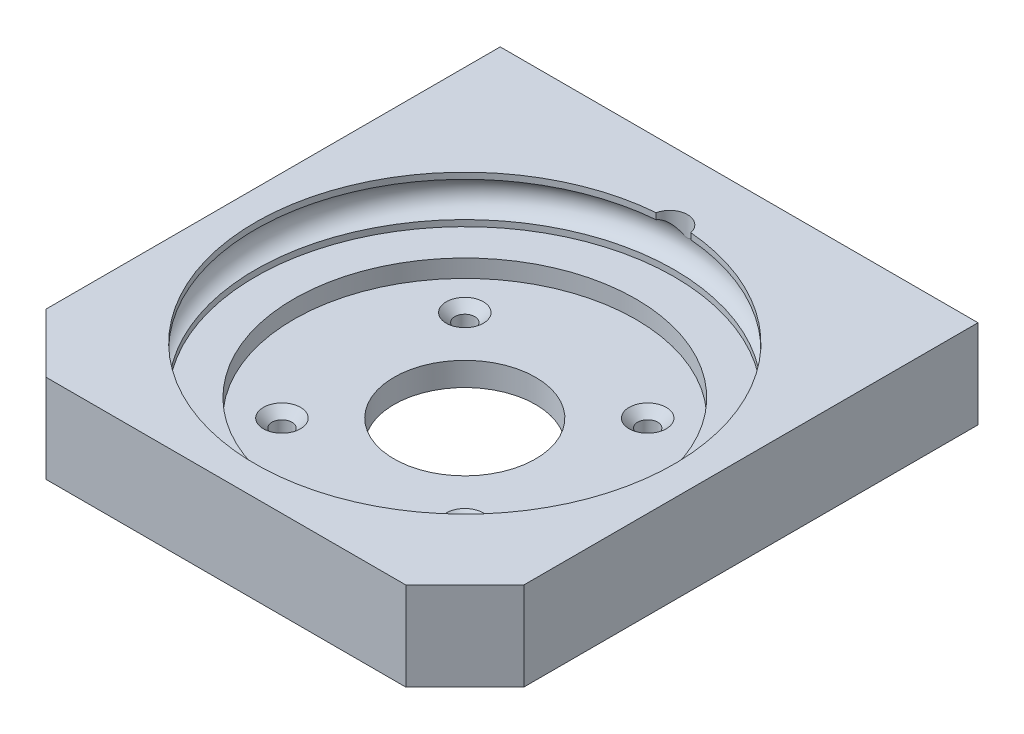
SolidWorks part; units mm, degrees
ref_plane "Front Plane" through (0, 0, 0) normal (0, 0, 1) x (1, 0, 0)
ref_plane "Top Plane" through (0, 0, 0) normal (0, 1, 0) x (1, 0, 0)
ref_plane "Right Plane" through (0, 0, 0) normal (1, 0, 0) x (0, 0, -1)
sketch "Sketch2" plane through (0, 0, 0) normal (0, 0, 1) x (1, 0, 0)
  line L0 (-29, 3) -> (-29, 0)
  line L1 (-29, 0) -> (-12, 0)
  line L2 (-12, 0) -> (-12, -4)
  line L3 (-12, -4) -> (-40.5, -4)
  line L4 (0, 0) -> (0, 12.8376) construction
  line L6 (-29, 3) -> (-35.5, 3)
  line L7 (-35.5, 3) -> (-35.5, 11)
  line L8 (-35.5, 11) -> (-40.5, 11)
  line L9 (-40.5, 11) -> (-40.5, -4)
  dimension "D1" = 24
  dimension "D2" = 58
  dimension "D3" = 71
  dimension "D4" = 5
  dimension "D5" = 4
  dimension "D6" = 3
  dimension "D7" = 8
revolve "Revolve1" add sketch "Sketch2" angle 360 about L4
sketch "Sketch3" plane through (0, 0, 0) normal (0, 1, 0) x (1, 0, 0)
  line L1 (-13, -13) -> (13, -13) construction
  line L2 (-13, -13) -> (-13, 13) construction
  line L3 (-13, 13) -> (13, 13) construction
  line L4 (13, -13) -> (13, 13) construction
  line L5 (-13, -13) -> (13, 13) construction
  line L6 (-13, 13) -> (13, -13) construction
  line L7 (-15.5, -15.5) -> (15.5, -15.5) construction
  line L8 (-15.5, -15.5) -> (-15.5, 15.5) construction
  line L9 (-15.5, 15.5) -> (15.5, 15.5) construction
  line L10 (15.5, -15.5) -> (15.5, 15.5) construction
  line L11 (-15.5, -15.5) -> (15.5, 15.5) construction
  line L12 (-15.5, 15.5) -> (15.5, -15.5) construction
  circle A0 centre (-13, 13) radius 1.25 construction
  circle A1 centre (13, 13) radius 1.25 construction
  circle A2 centre (13, -13) radius 1.25 construction
  circle A3 centre (-13, -13) radius 1.25 construction
  circle A4 centre (-15.5, 15.5) radius 1.25
  circle A5 centre (15.5, 15.5) radius 1.25
  circle A6 centre (15.5, -15.5) radius 1.25
  circle A7 centre (-15.5, -15.5) radius 1.25
  point P0 (0, 0)
  point P10 (0, 0)
  dimension "D2" = 2.5
  dimension "D1" = 26
  dimension "D3" = 31
extrude "Cut-Extrude1" cut sketch "Sketch3" against normal through all
sketch "Sketch4" plane through (0, 11, 0) normal (0, 1, 0) x (1, 0, 0)
  circle A0 centre (0, 0) radius 35.5
  circle A1 centre (0, 35.5) radius 1
  circle A2 centre (2.0823, 35.7208) radius 1
  circle A3 centre (4.1749, 35.7958) radius 1
  circle A4 centre (6.2677, 35.7247) radius 1
  circle A5 centre (8.3504, 35.5077) radius 1
  circle A6 centre (10.4129, 35.146) radius 1
  circle A7 centre (12.4451, 34.6413) radius 1
  circle A8 centre (14.4372, 33.9961) radius 1
  circle A9 centre (16.3794, 33.2135) radius 1
  circle A10 centre (18.2623, 32.2973) radius 1
  circle A11 centre (20.0767, 31.252) radius 1
  circle A12 centre (21.8138, 30.0827) radius 1
  circle A13 centre (23.465, 28.795) radius 1
  circle A14 centre (25.0225, 27.3953) radius 1
  circle A15 centre (26.4785, 25.8904) radius 1
  circle A16 centre (27.8259, 24.2876) radius 1
  circle A17 centre (29.0583, 22.5947) radius 1
  circle A18 centre (30.1696, 20.8199) radius 1
  circle A19 centre (31.1543, 18.972) radius 1
  circle A20 centre (32.0078, 17.0598) radius 1
  circle A21 centre (32.7258, 15.0928) radius 1
  circle A22 centre (33.3049, 13.0805) radius 1
  circle A23 centre (33.7421, 11.0327) radius 1
  circle A24 centre (34.0355, 8.9593) radius 1
  circle A25 centre (34.1835, 6.8706) radius 1
  circle A26 centre (34.1854, 4.7766) radius 1
  circle A27 centre (34.0413, 2.6876) radius 1
  circle A28 centre (33.7518, 0.6138) radius 1
  circle A29 centre (33.3183, -1.4348) radius 1
  circle A30 centre (32.743, -3.4482) radius 1
  circle A31 centre (32.0286, -5.4166) radius 1
  circle A32 centre (31.1787, -7.3303) radius 1
  circle A33 centre (30.1974, -9.1801) radius 1
  circle A34 centre (29.0894, -10.9569) radius 1
  circle A35 centre (27.8602, -12.6521) radius 1
  circle A36 centre (26.5157, -14.2574) radius 1
  circle A37 centre (25.0625, -15.765) radius 1
  circle A38 centre (23.5076, -17.1676) radius 1
  circle A39 centre (21.8588, -18.4583) radius 1
  circle A40 centre (20.1239, -19.6309) radius 1
  circle A41 centre (18.3114, -20.6795) radius 1
  circle A42 centre (16.4302, -21.5992) radius 1
  circle A43 centre (14.4894, -22.3854) radius 1
  circle A44 centre (12.4986, -23.0343) radius 1
  circle A45 centre (10.4673, -23.5428) radius 1
  circle A46 centre (8.4054, -23.9083) radius 1
  circle A47 centre (6.3232, -24.1291) radius 1
  circle A48 centre (4.2305, -24.2041) radius 1
  circle A49 centre (2.1378, -24.133) radius 1
  circle A50 centre (0.0551, -23.9161) radius 1
  circle A51 centre (-2.0074, -23.5544) radius 1
  circle A52 centre (-4.0397, -23.0497) radius 1
  circle A53 centre (-6.0318, -22.4044) radius 1
  circle A54 centre (-7.974, -21.6218) radius 1
  circle A55 centre (-9.8569, -20.7056) radius 1
  circle A56 centre (-11.6713, -19.6603) radius 1
  circle A57 centre (-13.4083, -18.491) radius 1
  circle A58 centre (-15.0596, -17.2034) radius 1
  circle A59 centre (-16.617, -15.8037) radius 1
  circle A60 centre (-18.073, -14.2987) radius 1
  circle A61 centre (-19.4205, -12.6959) radius 1
  circle A62 centre (-20.6528, -11.003) radius 1
  circle A63 centre (-21.7641, -9.2282) radius 1
  circle A64 centre (-22.7489, -7.3803) radius 1
  circle A65 centre (-23.6024, -5.4681) radius 1
  circle A66 centre (-24.3204, -3.5011) radius 1
  circle A67 centre (-24.8994, -1.4888) radius 1
  circle A68 centre (-25.3367, 0.559) radius 1
  circle A69 centre (-25.63, 2.6323) radius 1
  circle A70 centre (-25.778, 4.7211) radius 1
  circle A71 centre (-25.78, 6.815) radius 1
  circle A72 centre (-25.6358, 8.904) radius 1
  circle A73 centre (-25.3463, 10.9779) radius 1
  circle A74 centre (-24.9129, 13.0265) radius 1
  circle A75 centre (-24.3376, 15.0399) radius 1
  circle A76 centre (-23.6232, 17.0083) radius 1
  circle A77 centre (-22.7733, 18.922) radius 1
  circle A78 centre (-21.7919, 20.7718) radius 1
  circle A79 centre (-20.6839, 22.5486) radius 1
  circle A80 centre (-19.4547, 24.2438) radius 1
  circle A81 centre (-18.1102, 25.8491) radius 1
  circle A82 centre (-16.657, 27.3567) radius 1
  circle A83 centre (-15.1022, 28.7593) radius 1
  circle A84 centre (-13.4533, 30.05) radius 1
  circle A85 centre (-11.7184, 31.2225) radius 1
  circle A86 centre (-9.906, 32.2712) radius 1
  circle A87 centre (-8.0248, 33.1909) radius 1
  circle A88 centre (-6.084, 33.9771) radius 1
  circle A89 centre (-4.0931, 34.626) radius 1
  circle A90 centre (-2.0618, 35.1345) radius 1
  circle A91 centre (0, 0) radius 35.5 construction
  dimension "D1" = 2
  dimension "D3" = 0.094
  dimension "D2" = 90
sketch "Sketch5" plane through (0, 0, 0) normal (0, 0, 1) x (1, 0, 0)
  line L0 (35.5, 7) -> (34.75, 7) construction
  line L1 (35.5, 3) -> (35.5, 11) construction
  line L2 (0, 0) -> (0, -3.9123) construction
  circle A0 centre (34.75, 7) radius 3.05
  dimension "D1" = 6.1
  dimension "D2" = 0.75
revolve "Cut-Revolve1" cut sketch "Sketch5" angle 360 about L2
ref_plane "Plane1" through (0, 7, 0) normal (0, 1, 0) x (1, 0, 0)
sketch "Sketch6" plane through (0, 7, 0) normal (0, 1, 0) x (1, 0, 0)
  circle A0 centre (0, 34.75) radius 3
  circle A1 centre (0, 0) radius 35.5 construction
  dimension "D1" = 6
  dimension "D2" = 0.75
extrude "Cut-Extrude2" cut sketch "Sketch6" along normal blind 10
sketch "Sketch8" plane through (0, -4, 0) normal (0, -1, 0) x (1, 0, 0)
  line L1 (-40.5, -40.5) -> (40.5, -40.5)
  line L2 (-40.5, -40.5) -> (-40.5, 40.5)
  line L3 (-40.5, 40.5) -> (40.5, 40.5)
  line L4 (40.5, -40.5) -> (40.5, 40.5)
  line L5 (-40.5, -40.5) -> (40.5, 40.5) construction
  line L6 (-40.5, 40.5) -> (40.5, -40.5) construction
  circle A0 centre (0, 0) radius 40.5 construction
  circle A1 centre (0, 0) radius 40.5
  point P0 (0, 0)
  circle M10 centre (0, 0) radius 40.5
extrude "Boss-Extrude1" add sketch "Sketch8" against normal up to surface (15 mm away) contours L3 L2 L1 M10 | L1 L4 L3 M10 | L2 L1 M10 | L4 L3 M10
hole_wizard "CBORE for M4 Hex Socket Head Cap Screw1" positions "Sketch9" profile "Sketch10" counterbore size "M4" standard "ISO"
sketch "Sketch9" plane through (0, 11, 0) normal (0, 1, 0) x (1, 0, 0)
  line L0 (0, 0) -> (0, -7.0915) construction
  line L3 (40.5, 40.5) -> (-40.5, 40.5) construction
  point P0 (-27.5, 33)
  point P7 (27.5, 33)
  dimension "D1" = 55
  dimension "D2" = 7.5
sketch "Sketch10" plane through (-27.5, 11, -33) normal (1, 0, 0) x (0, 0, 1)
  line L0 (0, 0) -> (0, 15)
  line L1 (0, 15) -> (2.25, 15)
  line L3 (2.25, 15) -> (2.25, 4.4)
  line L4 (2.25, 4.4) -> (4, 4.4)
  line L5 (4, 4.4) -> (4, 0)
  line L7 (4, 0) -> (0, 0)
  line L11 (0, -6.35) -> (0, 107.95) construction
  dimension "Thru Hole Dia." = 4.5
  dimension "Thru Hole Depth" = 15
  dimension "C'Bore Dia." = 8
  dimension "C'Bore Depth" = 4.4
chamfer "Chamfer1" distance 10 angle 45 2 edges at (-40.5, 3.5, 40.5) (40.5, 3.5, 40.5)
hole_wizard "CSK for M3 Countersunk Flat Head Screw1" positions "Sketch13" profile "Sketch14" countersink size "M3" standard "ISO" end condition through all
sketch "Sketch13" plane through (0, 0, 0) normal (0, 1, 0) x (1, 0, 0)
  point P12 (-15.5, 15.5)
  point P15 (15.5, 15.5)
  point P18 (15.5, -15.5)
  point P21 (-15.5, -15.5)
sketch "Sketch14" plane through (-15.5, 0, -15.5) normal (1, 0, 0) x (0, 0, 1)
  line L0 (0, 0) -> (0, 4)
  line L1 (0, 4) -> (1.7, 4)
  line L2 (1.7, 4) -> (1.7, 1.45)
  line L3 (1.7, 1.45) -> (3.15, 0)
  line L5 (3.15, 0) -> (0, 0)
  line L6 (-1.7, 1.45) -> (-3.15, 0) construction
  line L11 (0, -6.35) -> (0, 107.95) construction
  dimension "Thru Hole Dia." = 3.4
  dimension "Thru Hole Depth" = 4
  dimension "Near C'Sink Dia." = 6.3
  dimension "Near C'Sink Angle" = 90
sketch "Sketch15" plane through (0, 0, -40.5) normal (0, 0, -1) x (-1, 0, 0)
  line L4 (40.5, 11) -> (-40.5, 11)
  line L5 (-40.5, 11) -> (-40.5, -4)
  line L6 (-40.5, -4) -> (40.5, -4)
  line L7 (40.5, -4) -> (40.5, 11)
  line L8 (40.5, 11) -> (-40.5, 11)
  line L9 (-40.5, 11) -> (-40.5, -4)
  line L10 (-40.5, -4) -> (40.5, -4)
  line L11 (40.5, -4) -> (40.5, 11)
  dimension "D1" = 0
extrude "Boss-Extrude2" add sketch "Sketch15" along normal blind 6
sketch "Sketch16" plane through (0, 0, -46.5) normal (0, 0, -1) x (-1, 0, 0)
  line L0 (0, 0) -> (0, 26.7697) construction
  line L1 (40.5, 11) -> (-40.5, 11) construction
  circle A0 centre (-27.5, 3.5) radius 2.95
  circle A1 centre (27.5, 3.5) radius 2.95
  dimension "D1" = 55
  dimension "D2" = 7.5
  dimension "D3" = 5.9
extrude "Cut-Extrude3" cut sketch "Sketch16" against normal blind 6.8
hole_wizard "M4 Clearance Hole1" positions "Sketch17" profile "Sketch19" hole size "M4" standard "ISO"
sketch "Sketch17" plane through (0, 0, -46.5) normal (0, 0, -1) x (-1, 0, 0)
  point P0 (-27.5, 3.5)
  point P3 (27.5, 3.5)
sketch "Sketch19" plane through (27.5, 3.5, -46.5) normal (1, 0, 0) x (0, 1, 0)
  line L0 (0, 0) -> (0, 15.4421)
  line L1 (0, 15.4421) -> (2.4, 14)
  line L2 (2.4, 14) -> (2.4, 0)
  line L5 (2.4, 0) -> (0, 0)
  line L10 (0, 15.4421) -> (-2.4, 14) construction
  line L11 (0, -6.35) -> (0, 107.95) construction
  dimension "Hole Dia." = 4.8
  dimension "Hole Depth" = 14
  dimension "Drill Angle" = 118
